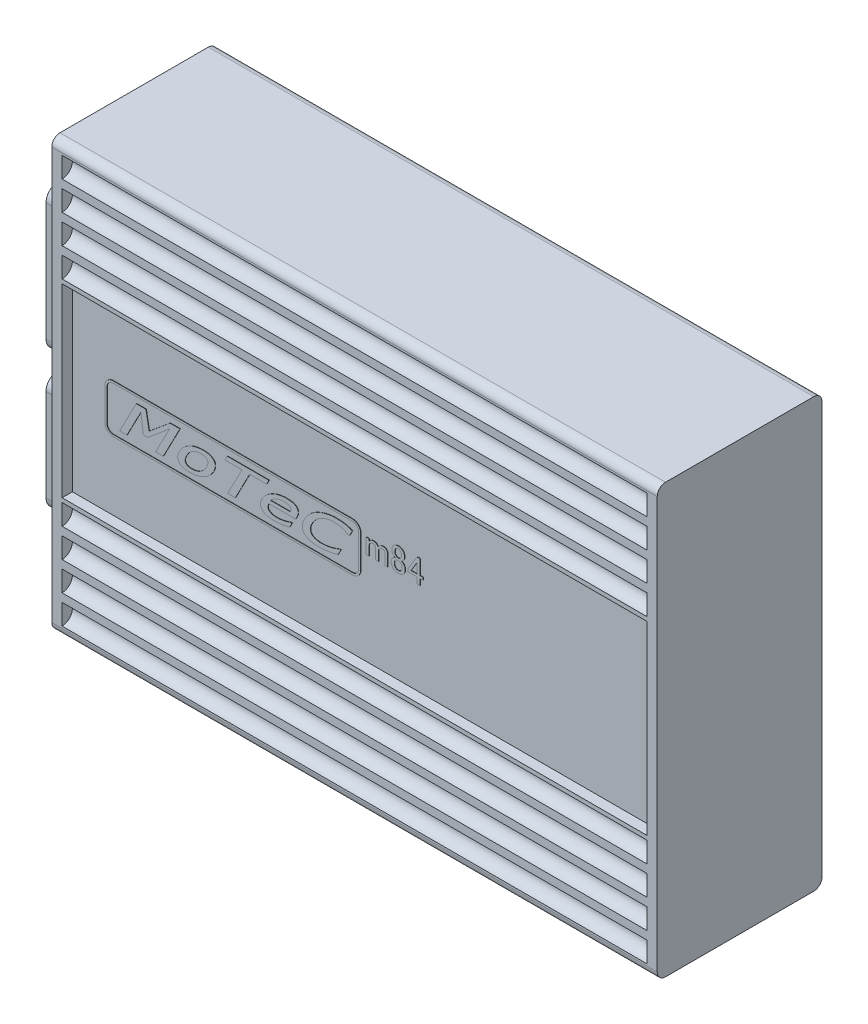
SolidWorks part; units mm, degrees
material "ｽﾁﾚﾝ ﾌﾞﾀｼﾞｴﾝｺﾞﾑ(SBR)"
ref_plane "正面" through (0, 0, 0) normal (0, 0, 1) x (1, 0, 0)
ref_plane "平面" through (0, 0, 0) normal (0, 1, 0) x (1, 0, 0)
ref_plane "右側面" through (0, 0, 0) normal (1, 0, 0) x (0, 0, -1)
sketch "ｽｹｯﾁ1" plane through (0, 0, 0) normal (0, 0, 1) x (1, 0, 0)
  line L1 (-73.5, -52) -> (73.5, -52)
  line L2 (-73.5, -52) -> (-73.5, 52)
  line L3 (-73.5, 52) -> (73.5, 52)
  line L4 (73.5, -52) -> (73.5, 52)
  line L5 (-73.5, -52) -> (73.5, 52) construction
  line L6 (-73.5, 52) -> (73.5, -52) construction
  point P0 (0, 0)
extrude "ﾎﾞｽ - 押し出し1" add sketch "ｽｹｯﾁ1" along normal blind 40
fillet "ﾌｨﾚｯﾄ1" radius 2 4 edges at (0, -52, 0) (0, -52, 40) (0, 52, 0) (0, 52, 40)
sketch "ｽｹｯﾁ5" plane through (0, 0, 0) normal (0, 0, -1) x (-1, 0, 0)
  line L0 (73.5, 50) -> (73.5, -50) construction
  line L1 (-73.5, 22.5) -> (73.5, 22.5)
  line L2 (-73.5, 22.5) -> (-73.5, -22.5)
  line L3 (-73.5, -22.5) -> (73.5, -22.5)
  line L4 (73.5, 22.5) -> (73.5, -22.5)
  line L5 (-73.5, 22.5) -> (73.5, -22.5) construction
  line L6 (-73.5, -22.5) -> (73.5, 22.5) construction
  point P0 (0, 0)
extrude "ｶｯﾄ - 押し出し1" cut sketch "ｽｹｯﾁ5" against normal blind 2.5
sketch "ｽｹｯﾁ6" plane through (-73.5, 0, 0) normal (-1, 0, 0) x (0, 0, 1)
  line L0 (0, 49.5) -> (0, 44.5)
  line L1 (0, 42.5) -> (0, 37.5)
  line L2 (0, 35.5) -> (0, 30.5)
  line L3 (0, 50) -> (0, 22.5) construction
  line L4 (0, 28.5) -> (0, 23.5)
  line L7 (40, 28.5) -> (40, 23.5)
  line L8 (40, 35.5) -> (40, 30.5)
  line L9 (40, 42.5) -> (40, 37.5)
  line L10 (40, 49.5) -> (40, 44.5)
  arc A0 (0, 44.5) -> (0, 49.5) centre (0, 47) ccw
  arc A1 (0, 37.5) -> (0, 42.5) centre (0, 40) ccw
  arc A2 (0, 30.5) -> (0, 35.5) centre (0, 33) ccw
  arc A3 (0, 23.5) -> (0, 28.5) centre (0, 26) ccw
  arc A4 (40, 23.5) -> (40, 28.5) centre (40, 26) cw
  arc A5 (40, 30.5) -> (40, 35.5) centre (40, 33) cw
  arc A6 (40, 37.5) -> (40, 42.5) centre (40, 40) cw
  arc A7 (40, 44.5) -> (40, 49.5) centre (40, 47) cw
extrude "ｶｯﾄ - 押し出し2" cut sketch "ｽｹｯﾁ6" against normal through all
mirror "ﾐﾗｰ1" about plane through (0, 0, 0) normal (0, 1, 0) of "ｶｯﾄ - 押し出し2"
sketch "ｽｹｯﾁ7" plane through (0, 0, 40) normal (0, 0, 1) x (1, 0, 0)
  line L0 (73.5, -23.5) -> (73.5, 23.5) construction
  line L1 (-73.5, -22.5) -> (73.5, -22.5)
  line L2 (-73.5, -22.5) -> (-73.5, 22.5)
  line L3 (-73.5, 22.5) -> (73.5, 22.5)
  line L4 (73.5, -22.5) -> (73.5, 22.5)
  line L5 (-73.5, -22.5) -> (73.5, 22.5) construction
  line L6 (-73.5, 22.5) -> (73.5, -22.5) construction
  point P0 (0, 0)
extrude "ｶｯﾄ - 押し出し3" cut sketch "ｽｹｯﾁ7" against normal blind 2.5
sketch "ｽｹｯﾁ8" plane through (-73.5, 0, 0) normal (-1, 0, 0) x (0, 0, 1)
  line L0 (2, -52) -> (38, -52)
  line L2 (40, -50) -> (40, 50)
  line L3 (38, 52) -> (2, 52)
  line L4 (0, 50) -> (0, -50)
  arc A0 (38, -52) -> (40, -50) centre (38, -50) ccw
  arc A1 (0, -50) -> (2, -52) centre (2, -50) ccw
  arc A2 (2, 52) -> (0, 50) centre (2, 50) ccw
  arc A3 (40, 50) -> (38, 52) centre (38, 50) ccw
  dimension "D1" = 2
extrude "ﾎﾞｽ - 押し出し4" add sketch "ｽｹｯﾁ8" against normal blind 2.5
sketch "ｽｹｯﾁ9" plane through (73.5, 0, 0) normal (1, 0, 0) x (0, 0, -1)
  line L0 (-38, -52) -> (-2, -52)
  line L2 (0, -50) -> (0, 50)
  line L3 (-2, 52) -> (-38, 52)
  line L4 (-40, 50) -> (-40, -50)
  arc A1 (-38, 52) -> (-40, 50) centre (-38, 50) ccw
  arc A2 (0, 50) -> (-2, 52) centre (-2, 50) ccw
  arc A3 (-2, -52) -> (0, -50) centre (-2, -50) ccw
  arc A4 (-40, -50) -> (-38, -52) centre (-38, -50) ccw
  dimension "D1" = 2
extrude "ﾎﾞｽ - 押し出し5" add sketch "ｽｹｯﾁ9" against normal blind 2.5
sketch "ｽｹｯﾁ10" plane through (0, 0, 37.5) normal (0, 0, 1) x (1, 0, 0)
  line L0 (-61, 5.38) -> (-2.9, 5.38)
  line L1 (-61, 5.88) -> (-2.9, 5.88)
  line L2 (-48.818, -3.88) -> (-50.6846, -3.88)
  line L3 (-61, -5.38) -> (-2.9, -5.38)
  line L4 (-50.6846, -3.88) -> (-47.2953, 2.6347)
  line L5 (-62.5, -3.88) -> (-62.5, 3.88)
  line L6 (-63, -3.88) -> (-63, 3.88)
  line L7 (-1.4, 3.88) -> (-1.4, -3.88)
  line L8 (-2.9, -5.88) -> (-61, -5.88)
  line L9 (-0.9, 3.88) -> (-0.9, -3.88)
  line L10 (-47.2953, 2.6347) -> (-52.5742, -1.8169)
  line L11 (-52.5742, -1.8169) -> (-53.6672, -1.8169)
  line L12 (-53.6672, -1.8169) -> (-54.2704, 2.6347)
  line L13 (-54.2704, 2.6347) -> (-57.6598, -3.88)
  line L14 (-57.6598, -3.88) -> (-59.4281, -3.88)
  line L15 (-59.4281, -3.88) -> (-55.3895, 3.8811)
  line L16 (-55.3895, 3.8811) -> (-53.0363, 3.8811)
  line L17 (-53.0363, 3.8811) -> (-52.2641, -0.3464)
  line L18 (-52.2641, -0.3464) -> (-47.1924, 3.8811)
  line L19 (-47.1924, 3.8811) -> (-44.7793, 3.8811)
  line L20 (-44.7793, 3.8811) -> (-48.818, -3.88)
  line L21 (-23.7279, 2.8005) -> (-27.8541, 2.8005)
  line L22 (-27.8541, 2.8005) -> (-31.3309, -3.88)
  line L23 (-31.3309, -3.88) -> (-33.1975, -3.88)
  line L24 (-33.1975, -3.88) -> (-29.7207, 2.8005)
  line L25 (-29.7207, 2.8005) -> (-33.8469, 2.8005)
  line L26 (-33.8469, 2.8005) -> (-33.285, 3.8811)
  line L27 (-33.285, 3.8811) -> (-23.1661, 3.8811)
  line L28 (-23.1661, 3.8811) -> (-23.7279, 2.8005)
  line L29 (-16.6837, -1.031) -> (-23.1677, -1.031)
  line L30 (-17.8457, -2.3081) -> (-17.5448, -2.3081)
  line L31 (-17.5448, -2.3081) -> (-18.1512, -3.4717)
  line L32 (-16.3675, -0.4231) -> (-16.6837, -1.031)
  line L33 (-22.7071, -0.1468) -> (-17.9915, -0.1468)
  line L34 (-2.9053, 3.3592) -> (-3.6052, 2.0145)
  line L35 (-3.6052, 2.0145) -> (-3.9475, 2.0145)
  line L36 (-6.0306, -2.0134) -> (-5.7005, -2.0134)
  line L37 (-5.7005, -2.0134) -> (-6.3944, -3.3458)
  arc A0 (-62.5, -3.88) -> (-61, -5.38) centre (-61, -3.88) ccw
  arc A1 (-63, -3.88) -> (-61, -5.88) centre (-61, -3.88) ccw
  arc A2 (-2.9, -5.38) -> (-1.4, -3.88) centre (-2.9, -3.88) ccw
  arc A3 (-2.9, -5.88) -> (-0.9, -3.88) centre (-2.9, -3.88) ccw
  arc A4 (-0.9, 3.88) -> (-2.9, 5.88) centre (-2.9, 3.88) ccw
  arc A5 (-1.4, 3.88) -> (-2.9, 5.38) centre (-2.9, 3.88) ccw
  arc A6 (-61, 5.38) -> (-62.5, 3.88) centre (-61, 3.88) ccw
  arc A7 (-61, 5.88) -> (-63, 3.88) centre (-61, 3.88) ccw
  spline S0 degree 3 poles (-36.5777, -0.9358) (-36.7009, -1.173) (-36.9152, -1.5135) (-37.2513, -1.9317) (-37.5302, -2.2278) (-37.8372, -2.5041) (-38.1693, -2.764) (-38.5283, -3.0057) (-38.9122, -3.2263) (-39.3132, -3.4265) (-39.7277, -3.6013) (-40.1536, -3.7457) (-40.5887, -3.8684) (-41.0349, -3.9619) (-41.649, -4.05) (-42.1174, -4.0762) (-42.4323, -4.0765) knots 0 0 0 0 0.11486 0.17245 0.230506 0.289545 0.349887 0.411704 0.475483 0.540129 0.604325 0.668756 0.733403 0.798605 0.864633 1 1 1 1
  spline S1 degree 3 poles (-42.4323, -4.0765) (-42.5834, -4.0783) (-42.8056, -4.0683) (-43.0953, -4.0494) (-43.2985, -4.0256) (-43.4923, -3.9973) (-43.6765, -3.96) (-43.8518, -3.9174) (-44.0177, -3.8681) (-44.1746, -3.8138) (-44.3211, -3.7497) (-44.4591, -3.6817) (-44.587, -3.6058) (-44.7062, -3.5246) (-44.8151, -3.4352) (-44.9152, -3.3398) (-45.0063, -3.2387) (-45.0858, -3.1309) (-45.1562, -3.0187) (-45.2118, -2.9001) (-45.2596, -2.778) (-45.2917, -2.6499) (-45.3182, -2.5179) (-45.3269, -2.3804) (-45.3297, -2.2389) (-45.3179, -2.0927) (-45.2961, -1.9415) (-45.2643, -1.7849) (-45.2188, -1.6238) (-45.1639, -1.4575) (-45.0707, -1.2253) (-44.9886, -1.0518) (-44.9282, -0.9358) knots 0 0 0 0 0.08649 0.127322 0.166248 0.203584 0.23944 0.273835 0.30684 0.338533 0.36885 0.398333 0.426574 0.453963 0.480825 0.507145 0.533083 0.558634 0.58376 0.608791 0.633551 0.65871 0.684341 0.710499 0.737457 0.765367 0.794373 0.824886 0.856804 0.89016 0.925145 1 1 1 1
  spline S2 degree 3 poles (-44.9282, -0.9358) (-44.8022, -0.6955) (-44.5877, -0.3482) (-44.2489, 0.0764) (-43.9702, 0.375) (-43.6668, 0.6536) (-43.3382, 0.9124) (-42.9843, 1.1516) (-42.6081, 1.372) (-42.2138, 1.5683) (-41.8079, 1.7417) (-41.3903, 1.8851) (-40.9637, 2.0059) (-40.5266, 2.0973) (-39.9262, 2.1872) (-39.4676, 2.2089) (-39.1596, 2.211) knots 0 0 0 0 0.117897 0.176741 0.23572 0.295189 0.355492 0.41727 0.480633 0.544754 0.608501 0.672263 0.736447 0.800971 0.86614 1 1 1 1
  spline S3 degree 3 poles (-39.1596, 2.211) (-39.0055, 2.212) (-38.7785, 2.2044) (-38.4828, 2.1817) (-38.2753, 2.1594) (-38.0778, 2.128) (-37.8898, 2.0917) (-37.7107, 2.0491) (-37.5419, 1.998) (-37.3816, 1.9418) (-37.2315, 1.8774) (-37.0912, 1.8064) (-36.9598, 1.7299) (-36.8387, 1.645) (-36.7263, 1.5549) (-36.624, 1.4574) (-36.5325, 1.3533) (-36.4501, 1.2439) (-36.3803, 1.1288) (-36.3192, 1.0103) (-36.2719, 0.8865) (-36.2349, 0.7587) (-36.2085, 0.6268) (-36.1952, 0.49) (-36.1917, 0.3489) (-36.2017, 0.2032) (-36.2217, 0.0534) (-36.2531, -0.1007) (-36.2938, -0.26) (-36.3488, -0.4229) (-36.4364, -0.6522) (-36.5191, -0.8216) (-36.5777, -0.9358) knots 0 0 0 0 0.087469 0.128832 0.16828 0.205905 0.2423 0.276956 0.310309 0.342367 0.373332 0.402945 0.431585 0.459541 0.4868 0.513298 0.539635 0.565367 0.590919 0.615986 0.640903 0.665995 0.691455 0.717145 0.74387 0.771515 0.799937 0.829554 0.860759 0.893179 0.927103 1 1 1 1
  spline S4 degree 3 poles (-38.346, -0.9358) (-38.2574, -0.7704) (-38.1489, -0.5248) (-38.0457, -0.2002) (-38.0049, 0.0143) (-37.9926, 0.211) (-38.0094, 0.3913) (-38.0597, 0.5536) (-38.1369, 0.6994) (-38.2448, 0.8249) (-38.3747, 0.9354) (-38.5316, 1.0255) (-38.7113, 1.1012) (-38.9167, 1.1584) (-39.2379, 1.2147) (-39.4932, 1.2305) (-39.6708, 1.2286) knots 0 0 0 0 0.165351 0.236136 0.299935 0.35732 0.409486 0.458578 0.506215 0.55393 0.603552 0.655936 0.712748 0.775154 0.843472 1 1 1 1
  spline S5 degree 3 poles (-39.6708, 1.2286) (-39.8529, 1.2297) (-40.1234, 1.2126) (-40.4773, 1.1597) (-40.7328, 1.103) (-40.9807, 1.0286) (-41.2218, 0.9397) (-41.4561, 0.8354) (-41.6821, 0.7134) (-41.9013, 0.5755) (-42.11, 0.417) (-42.309, 0.2388) (-42.4999, 0.0427) (-42.6788, -0.1755) (-42.9131, -0.4938) (-43.0653, -0.7549) (-43.1599, -0.9358) knots 0 0 0 0 0.125748 0.186879 0.246987 0.306363 0.365517 0.424368 0.483349 0.542766 0.603061 0.664139 0.727124 0.791879 0.858893 1 1 1 1
  spline S6 degree 3 poles (-43.1599, -0.9358) (-43.2444, -1.1024) (-43.3583, -1.3453) (-43.4595, -1.6697) (-43.5022, -1.8833) (-43.5179, -2.0794) (-43.5036, -2.2592) (-43.4591, -2.4214) (-43.3855, -2.5663) (-43.2836, -2.6915) (-43.1582, -2.8004) (-43.0096, -2.8929) (-42.8366, -2.9656) (-42.6417, -3.0243) (-42.335, -3.08) (-42.0911, -3.096) (-41.9211, -3.0941) knots 0 0 0 0 0.168476 0.240795 0.305611 0.364297 0.417506 0.467272 0.514892 0.562763 0.611762 0.663944 0.719687 0.780349 0.846975 1 1 1 1
  spline S7 degree 3 poles (-41.9211, -3.0941) (-41.7331, -3.0918) (-41.4531, -3.0796) (-41.0877, -3.0195) (-40.8225, -2.963) (-40.5649, -2.885) (-40.3148, -2.7913) (-40.0706, -2.6823) (-39.8349, -2.5547) (-39.6073, -2.4111) (-39.3924, -2.2487) (-39.1871, -2.0723) (-38.995, -1.8776) (-38.8135, -1.6672) (-38.5852, -1.3596) (-38.4377, -1.1088) (-38.346, -0.9358) knots 0 0 0 0 0.128096 0.190164 0.251852 0.312564 0.373178 0.433506 0.494435 0.555497 0.616445 0.67768 0.739494 0.802466 0.866689 1 1 1 1
  spline S8 degree 3 poles (-23.1677, -1.031) (-23.239, -1.1708) (-23.3273, -1.3838) (-23.38, -1.6756) (-23.3836, -1.8779) (-23.3558, -2.064) (-23.2898, -2.2835) (-23.1916, -2.4213) (-23.1124, -2.4939) knots 0 0 0 0 0.300432 0.436419 0.564515 0.685087 0.794857 1 1 1 1
  spline S9 degree 3 poles (-23.1124, -2.4939) (-23.0171, -2.5853) (-22.8472, -2.6978) (-22.5932, -2.8134) (-22.3737, -2.881) (-22.1311, -2.9328) (-21.7617, -2.9823) (-21.4713, -2.9964) (-21.2704, -2.9958) knots 0 0 0 0 0.202 0.310705 0.427794 0.554064 0.691352 1 1 1 1
  spline S10 degree 3 poles (-21.2704, -2.9958) (-20.9645, -2.9964) (-20.4966, -2.9651) (-19.8657, -2.8697) (-19.4578, -2.787) (-19.1335, -2.7124) (-18.904, -2.6537) (-18.6896, -2.5968) (-18.4904, -2.5414) (-18.3075, -2.4814) (-18.0917, -2.4113) (-17.9411, -2.3484) (-17.8457, -2.3081) knots 0 0 0 0 0.261145 0.399928 0.544803 0.616587 0.684226 0.7471 0.806182 0.860786 0.911516 1 1 1 1
  spline S11 degree 3 poles (-18.1512, -3.4717) (-18.475, -3.5472) (-18.9516, -3.6513) (-19.5758, -3.7713) (-20.0167, -3.8464) (-20.4491, -3.9062) (-21.0272, -3.9606) (-21.4634, -3.9803) (-21.7554, -3.9782) knots 0 0 0 0 0.273424 0.401082 0.522686 0.641161 0.759937 1 1 1 1
  spline S12 degree 3 poles (-21.7554, -3.9782) (-21.9325, -3.9782) (-22.1927, -3.9728) (-22.5319, -3.952) (-22.7704, -3.9305) (-22.9983, -3.9034) (-23.2158, -3.8692) (-23.4231, -3.8303) (-23.6188, -3.7821) (-23.8044, -3.7301) (-23.9792, -3.6721) (-24.1438, -3.6078) (-24.2976, -3.5371) (-24.4413, -3.4607) (-24.5728, -3.3758) (-24.6951, -3.287) (-24.8059, -3.1914) (-24.9057, -3.0909) (-24.9926, -2.984) (-25.0668, -2.8714) (-25.1282, -2.7529) (-25.1775, -2.6295) (-25.2152, -2.5012) (-25.2374, -2.3672) (-25.2483, -2.228) (-25.2465, -2.0837) (-25.2323, -1.9339) (-25.2059, -1.779) (-25.1677, -1.6188) (-25.1143, -1.4541) (-25.0259, -1.2206) (-24.9444, -1.0463) (-24.8838, -0.9297) knots 0 0 0 0 0.093747 0.137709 0.179862 0.220513 0.259166 0.296403 0.332074 0.365856 0.398404 0.429538 0.459352 0.487951 0.5156 0.542146 0.567881 0.592971 0.617041 0.640704 0.664206 0.687544 0.710946 0.734858 0.759308 0.78477 0.811155 0.838897 0.867868 0.898277 0.930422 1 1 1 1
  spline S13 degree 3 poles (-24.8838, -0.9297) (-24.7596, -0.6889) (-24.54, -0.3451) (-24.1967, 0.0779) (-23.9084, 0.374) (-23.5931, 0.6518) (-23.2507, 0.9114) (-22.879, 1.1507) (-22.4832, 1.3708) (-22.0683, 1.5667) (-21.6416, 1.7397) (-21.2059, 1.8857) (-20.7601, 2.0035) (-20.3058, 2.0979) (-19.6825, 2.1863) (-19.2078, 2.2093) (-18.8895, 2.211) knots 0 0 0 0 0.114335 0.17179 0.229874 0.288677 0.349154 0.411205 0.475256 0.540323 0.604903 0.66963 0.734274 0.799596 0.865529 1 1 1 1
  spline S14 degree 3 poles (-18.8895, 2.211) (-18.6048, 2.2099) (-18.1943, 2.1957) (-17.6759, 2.1191) (-17.3417, 2.0438) (-17.0445, 1.9461) (-16.7843, 1.8273) (-16.5608, 1.6854) (-16.3763, 1.5207) (-16.2307, 1.3359) (-16.1253, 1.1324) (-16.062, 0.9113) (-16.0409, 0.6734) (-16.0638, 0.4205) (-16.1471, 0.0427) (-16.2705, -0.2361) (-16.3675, -0.4231) knots 0 0 0 0 0.180062 0.258847 0.330846 0.396281 0.456168 0.511145 0.562887 0.611718 0.659004 0.706791 0.756144 0.809012 0.866596 1 1 1 1
  spline S15 degree 3 poles (-17.9915, -0.1468) (-17.9461, -0.0555) (-17.8865, 0.0815) (-17.8527, 0.2692) (-17.8447, 0.3975) (-17.8607, 0.5196) (-17.8964, 0.6349) (-17.9525, 0.7434) (-18.0288, 0.8451) (-18.1292, 0.9365) (-18.2534, 1.0168) (-18.4034, 1.0814) (-18.5763, 1.1374) (-18.7753, 1.1766) (-19.0885, 1.2199) (-19.3376, 1.2281) (-19.5112, 1.2286) knots 0 0 0 0 0.116957 0.168662 0.217232 0.263196 0.308491 0.3545 0.402079 0.452957 0.508728 0.570212 0.638975 0.71601 0.801566 1 1 1 1
  spline S16 degree 3 poles (-19.5112, 1.2286) (-19.6901, 1.2296) (-19.9551, 1.2158) (-20.3024, 1.173) (-20.5519, 1.1269) (-20.7942, 1.0681) (-21.0289, 0.9984) (-21.2559, 0.9133) (-21.473, 0.8155) (-21.6796, 0.7097) (-21.8724, 0.5999) (-22.0503, 0.4864) (-22.2113, 0.3673) (-22.3597, 0.2473) (-22.5306, 0.0813) (-22.6436, -0.052) (-22.7071, -0.1468) knots 0 0 0 0 0.148913 0.22062 0.291229 0.360047 0.428112 0.494978 0.561724 0.626315 0.68814 0.746401 0.801873 0.85484 0.905156 1 1 1 1
  spline S17 degree 3 poles (-6.3944, -3.3458) (-6.5902, -3.3974) (-6.8702, -3.4618) (-7.2185, -3.5552) (-7.4427, -3.6129) (-7.6661, -3.6705) (-8.0166, -3.7476) (-8.2963, -3.8041) (-8.4943, -3.8416) knots 0 0 0 0 0.281526 0.399182 0.501308 0.603258 0.719903 1 1 1 1
  spline S18 degree 3 poles (-8.4943, -3.8416) (-8.8676, -3.9077) (-9.3444, -3.9804) (-9.9296, -4.0402) (-10.362, -4.069) (-10.6924, -4.0756) (-10.9166, -4.0765) knots 0 0 0 0 0.466732 0.593333 0.724013 1 1 1 1
  spline S19 degree 3 poles (-10.9166, -4.0765) (-11.1224, -4.0785) (-11.4255, -4.0686) (-11.8221, -4.0444) (-12.1026, -4.0187) (-12.3717, -3.9842) (-12.6302, -3.9457) (-12.8771, -3.8954) (-13.1137, -3.8416) (-13.3375, -3.777) (-13.5489, -3.7043) (-13.7484, -3.6255) (-13.9349, -3.5367) (-14.1073, -3.4372) (-14.3203, -3.2993) (-14.4632, -3.1767) (-14.5515, -3.091) knots 0 0 0 0 0.160141 0.235948 0.30913 0.379362 0.447054 0.512417 0.575391 0.635885 0.693558 0.74931 0.80274 0.854105 0.904135 1 1 1 1
  spline S20 degree 3 poles (-14.5515, -3.091) (-14.6332, -3.0081) (-14.7451, -2.8747) (-14.8665, -2.6775) (-14.9392, -2.5203) (-14.9998, -2.3557) (-15.0445, -2.1824) (-15.0729, -2.0004) (-15.0888, -1.8101) (-15.0872, -1.6112) (-15.0661, -1.4045) (-15.0293, -1.1901) (-14.9748, -0.9675) (-14.9028, -0.7377) (-14.7767, -0.413) (-14.6637, -0.1699) (-14.5792, -0.0071) knots 0 0 0 0 0.105347 0.15689 0.209093 0.261831 0.315407 0.370754 0.428362 0.488101 0.550445 0.616222 0.684847 0.757639 0.834008 1 1 1 1
  spline S21 degree 3 poles (-14.5792, -0.0071) (-14.4951, 0.1549) (-14.3581, 0.3917) (-14.1569, 0.6954) (-13.9973, 0.9172) (-13.8265, 1.1317) (-13.6473, 1.3406) (-13.4578, 1.5424) (-13.1913, 1.8022) (-12.8362, 2.1099) (-12.2254, 2.5699) (-11.7239, 2.8586) (-11.3786, 3.0338) knots 0 0 0 0 0.121978 0.18268 0.243425 0.304524 0.365875 0.427326 0.489476 0.614555 0.741086 1 1 1 1
  spline S22 degree 3 poles (-11.3786, 3.0338) (-11.0336, 3.2049) (-10.496, 3.4343) (-9.7453, 3.668) (-9.1567, 3.8174) (-8.5507, 3.9325) (-7.7204, 4.0477) (-7.0883, 4.0758) (-6.6645, 4.0776) knots 0 0 0 0 0.237239 0.359144 0.483968 0.611049 0.738924 1 1 1 1
  spline S23 degree 3 poles (-6.6645, 4.0776) (-6.3521, 4.0784) (-5.8883, 4.0593) (-5.2793, 3.995) (-4.8316, 3.9292) (-4.3774, 3.8355) (-3.7276, 3.6632) (-3.2372, 3.49) (-2.9053, 3.3592) knots 0 0 0 0 0.243327 0.361127 0.476764 0.595548 0.722064 1 1 1 1
  spline S24 degree 3 poles (-3.9475, 2.0145) (-4.1771, 2.184) (-4.5416, 2.4084) (-5.0614, 2.6382) (-5.4679, 2.7721) (-5.8967, 2.874) (-6.5232, 2.9708) (-7.0117, 2.9991) (-7.3461, 2.9969) knots 0 0 0 0 0.237578 0.354907 0.472536 0.593451 0.721574 1 1 1 1
  spline S25 degree 3 poles (-7.3461, 2.9969) (-7.6219, 2.9979) (-8.0311, 2.9755) (-8.5665, 2.9016) (-8.9542, 2.8232) (-9.3368, 2.7185) (-9.8553, 2.5457) (-10.2318, 2.368) (-10.4822, 2.2417) knots 0 0 0 0 0.253906 0.376619 0.497274 0.617832 0.741623 1 1 1 1
  spline S26 degree 3 poles (-10.4822, 2.2417) (-10.7045, 2.1261) (-11.028, 1.9227) (-11.4317, 1.6025) (-11.7296, 1.3332) (-12.0114, 1.0365) (-12.3621, 0.6006) (-12.5845, 0.2402) (-12.7156, -0.0117) knots 0 0 0 0 0.233293 0.354756 0.479582 0.607001 0.735458 1 1 1 1
  spline S27 degree 3 poles (-12.7156, -0.0117) (-12.7817, -0.1391) (-12.8725, -0.3274) (-12.9672, -0.5803) (-13.0257, -0.7553) (-13.0665, -0.9239) (-13.0951, -1.0849) (-13.1092, -1.2379) (-13.1092, -1.4273) (-13.0816, -1.6452) (-13.0027, -1.9554) (-12.8863, -2.1582) (-12.7862, -2.2682) knots 0 0 0 0 0.179369 0.260704 0.337327 0.409738 0.477214 0.541403 0.601498 0.713544 0.814809 1 1 1 1
  spline S28 degree 3 poles (-12.7862, -2.2682) (-12.6661, -2.3989) (-12.4496, -2.5673) (-12.1148, -2.7325) (-11.8285, -2.8305) (-11.5157, -2.9045) (-11.0545, -2.9772) (-10.6945, -2.996) (-10.4484, -2.9958) knots 0 0 0 0 0.211163 0.323577 0.443788 0.571197 0.706507 1 1 1 1
  spline S29 degree 3 poles (-10.4484, -2.9958) (-10.0792, -2.9962) (-9.5258, -2.9642) (-8.7927, -2.864) (-8.244, -2.7575) (-7.6933, -2.6209) (-6.9482, -2.3886) (-6.3948, -2.1771) (-6.0306, -2.0134) knots 0 0 0 0 0.24289 0.364219 0.486645 0.610525 0.737368 1 1 1 1
sketch "ｽｹｯﾁ11" plane through (0, 0, 37.5) normal (0, 0, 1) x (1, 0, 0)
  line L0 (1.1441, 0.0981) -> (0.448, 0.0981)
  line L1 (0.448, 0.0981) -> (0.448, 3.7593)
  line L2 (0.448, 3.7593) -> (1.1441, 3.7593)
  line L3 (1.1441, 3.7593) -> (1.1441, 3.2036)
  line L4 (5.6553, 2.8113) -> (5.6553, 0.0981)
  line L5 (5.6553, 0.0981) -> (4.9592, 0.0981)
  line L6 (4.9592, 0.0981) -> (4.9592, 2.6806)
  line L7 (3.3997, 2.419) -> (3.3997, 0.0981)
  line L8 (3.3997, 0.0981) -> (2.7036, 0.0981)
  line L9 (2.7036, 0.0981) -> (2.7036, 2.6479)
  line L10 (1.1441, 2.3864) -> (1.1441, 0.0981)
  line L11 (8.9655, 3.0075) -> (8.9655, 2.9421)
  line L12 (7.4618, 2.9421) -> (7.4618, 3.0075)
  line L13 (12.7902, 5.7534) -> (13.5421, 5.7534)
  line L14 (13.5421, 5.7534) -> (13.5421, 2.1575)
  line L15 (13.5421, 2.1575) -> (14.2286, 2.1575)
  line L16 (14.2286, 2.1575) -> (14.2286, 1.5388)
  line L17 (14.2286, 1.5388) -> (13.5421, 1.5388)
  line L18 (13.5421, 1.5388) -> (13.5421, 0.0981)
  line L19 (13.5421, 0.0981) -> (12.7684, 0.0981)
  line L20 (12.7684, 0.0981) -> (12.7684, 1.5388)
  line L21 (12.7684, 1.5388) -> (10.6, 1.5388)
  line L22 (10.6, 1.5388) -> (10.6, 2.1902)
  line L23 (10.6, 2.1902) -> (12.7902, 5.7534)
  line L24 (12.7684, 4.5439) -> (11.3192, 2.1575)
  line L25 (11.3192, 2.1575) -> (12.7684, 2.1575)
  line L26 (12.7684, 2.1575) -> (12.7684, 4.5439)
  spline S0 degree 3 poles (1.1441, 3.2036) (1.2091, 3.3006) (1.3165, 3.4324) (1.4761, 3.5832) (1.5982, 3.6709) (1.7237, 3.7398) (1.8965, 3.8054) (2.0336, 3.8248) (2.1248, 3.8247) knots 0 0 0 0 0.289076 0.420056 0.543346 0.660649 0.774007 1 1 1 1
  spline S1 degree 3 poles (2.1248, 3.8247) (2.2225, 3.8255) (2.3653, 3.8154) (2.5475, 3.7813) (2.6714, 3.7462) (2.7859, 3.7001) (2.9253, 3.6249) (3.0183, 3.5525) (3.0728, 3.4978) knots 0 0 0 0 0.28435 0.416051 0.539631 0.658871 0.775162 1 1 1 1
  spline S2 degree 3 poles (3.0728, 3.4978) (3.1259, 3.4441) (3.225, 3.3321) (3.3007, 3.2031) (3.3344, 3.1382) knots 0 0 0 0 0.508066 1 1 1 1
  spline S3 degree 3 poles (3.3344, 3.1382) (3.4009, 3.2461) (3.5142, 3.3952) (3.6946, 3.5595) (3.8391, 3.6553) (3.9921, 3.7317) (4.2138, 3.8066) (4.3918, 3.8235) (4.5112, 3.8247) knots 0 0 0 0 0.266156 0.390354 0.510676 0.628903 0.748675 1 1 1 1
  spline S4 degree 3 poles (4.5112, 3.8247) (4.5937, 3.8239) (4.715, 3.8171) (4.8701, 3.7856) (4.9763, 3.7531) (5.0759, 3.7116) (5.1981, 3.6443) (5.2797, 3.579) (5.3284, 3.5305) knots 0 0 0 0 0.277854 0.406706 0.531659 0.650908 0.768781 1 1 1 1
  spline S5 degree 3 poles (5.3284, 3.5305) (5.3803, 3.4787) (5.4513, 3.3967) (5.5288, 3.2784) (5.576, 3.1891) (5.6103, 3.0972) (5.6454, 2.9726) (5.6558, 2.876) (5.6553, 2.8113) knots 0 0 0 0 0.271081 0.399345 0.522112 0.643458 0.761079 1 1 1 1
  spline S6 degree 3 poles (4.9592, 2.6806) (4.9575, 2.7409) (4.949, 2.8568) (4.9009, 2.9629) (4.8708, 3.0075) knots 0 0 0 0 0.529898 1 1 1 1
  spline S7 degree 3 poles (4.8708, 3.0075) (4.81, 3.0685) (4.6691, 3.1722) (4.4969, 3.2038) (4.4131, 3.2036) knots 0 0 0 0 0.507506 1 1 1 1
  spline S8 degree 3 poles (4.4131, 3.2036) (4.3398, 3.2028) (4.2315, 3.1955) (4.0927, 3.1647) (3.9963, 3.131) (3.9039, 3.0907) (3.7882, 3.0211) (3.7089, 2.9578) (3.6613, 2.9094) knots 0 0 0 0 0.265315 0.391024 0.512886 0.634416 0.754828 1 1 1 1
  spline S9 degree 3 poles (3.6613, 2.9094) (3.5876, 2.833) (3.4593, 2.6878) (3.4011, 2.5024) (3.3997, 2.419) knots 0 0 0 0 0.564258 1 1 1 1
  spline S10 degree 3 poles (2.7036, 2.6479) (2.7041, 2.7153) (2.672, 2.8568) (2.5978, 2.9811) (2.5498, 3.0402) knots 0 0 0 0 0.468245 1 1 1 1
  spline S11 degree 3 poles (2.5498, 3.0402) (2.4931, 3.098) (2.3343, 3.1836) (2.1559, 3.2052) (2.0595, 3.2036) knots 0 0 0 0 0.45309 1 1 1 1
  spline S12 degree 3 poles (2.0595, 3.2036) (1.9447, 3.2054) (1.7132, 3.1598) (1.5193, 3.0255) (1.4384, 2.9421) knots 0 0 0 0 0.496526 1 1 1 1
  spline S13 degree 3 poles (1.4384, 2.9421) (1.3545, 2.8562) (1.2127, 2.6903) (1.1432, 2.4818) (1.1441, 2.3864) knots 0 0 0 0 0.561835 1 1 1 1
  spline S14 degree 3 poles (6.6772, 4.1843) (6.6768, 4.2995) (6.6912, 4.4688) (6.7381, 4.6867) (6.7896, 4.838) (6.8539, 4.9823) (6.9595, 5.1641) (7.0598, 5.287) (7.1349, 5.3611) knots 0 0 0 0 0.266281 0.391515 0.514598 0.635338 0.756207 1 1 1 1
  spline S15 degree 3 poles (7.1349, 5.3611) (7.2002, 5.4253) (7.3073, 5.5139) (7.4705, 5.6021) (7.6011, 5.6584) (7.7419, 5.7001) (7.9453, 5.7439) (8.1052, 5.7528) (8.2136, 5.7534) knots 0 0 0 0 0.233399 0.350616 0.471182 0.594645 0.723766 1 1 1 1
  spline S16 degree 3 poles (8.2136, 5.7534) (8.3232, 5.7551) (8.4841, 5.7404) (8.6912, 5.6974) (8.8344, 5.6494) (8.9701, 5.5899) (9.1412, 5.4928) (9.2549, 5.3974) (9.3251, 5.3284) knots 0 0 0 0 0.268573 0.395226 0.518308 0.638476 0.758247 1 1 1 1
  spline S17 degree 3 poles (9.3251, 5.3284) (9.3942, 5.2575) (9.4892, 5.1424) (9.5874, 4.969) (9.6459, 4.8292) (9.694, 4.6812) (9.7374, 4.466) (9.7518, 4.2987) (9.75, 4.1843) knots 0 0 0 0 0.237237 0.354867 0.475589 0.599283 0.726563 1 1 1 1
  spline S18 degree 3 poles (9.75, 4.1843) (9.7496, 4.0948) (9.7399, 3.9612) (9.6961, 3.7908) (9.6544, 3.6685) (9.5976, 3.5525) (9.5084, 3.4007) (9.4204, 3.3) (9.3578, 3.2363) knots 0 0 0 0 0.255144 0.378267 0.499952 0.622216 0.745323 1 1 1 1
  spline S19 degree 3 poles (9.3578, 3.2363) (9.3031, 3.1841) (9.1835, 3.0859) (9.0392, 3.0294) (8.9655, 3.0075) knots 0 0 0 0 0.495336 1 1 1 1
  spline S20 degree 3 poles (8.9655, 2.9421) (9.0661, 2.92) (9.2702, 2.8364) (9.4397, 2.6957) (9.5212, 2.6152) knots 0 0 0 0 0.472373 1 1 1 1
  spline S21 degree 3 poles (9.5212, 2.6152) (9.5855, 2.5508) (9.6734, 2.4449) (9.7619, 2.2847) (9.8183, 2.1578) (9.86, 2.0219) (9.904, 1.8266) (9.9129, 1.6731) (9.9135, 1.5691) knots 0 0 0 0 0.238094 0.356648 0.477581 0.600363 0.727833 1 1 1 1
  spline S22 degree 3 poles (9.9135, 1.5691) (9.9138, 1.4636) (9.8992, 1.3074) (9.852, 1.1064) (9.8021, 0.9634) (9.7365, 0.8269) (9.6294, 0.6512) (9.5306, 0.5307) (9.4558, 0.4577) knots 0 0 0 0 0.256258 0.379192 0.500731 0.623509 0.746244 1 1 1 1
  spline S23 degree 3 poles (9.4558, 0.4577) (9.3839, 0.3872) (9.2639, 0.2913) (9.0813, 0.1952) (8.9312, 0.1362) (8.7694, 0.0881) (8.5294, 0.0453) (8.3421, 0.0307) (8.2136, 0.0327) knots 0 0 0 0 0.224285 0.339224 0.458169 0.582683 0.714303 1 1 1 1
  spline S24 degree 3 poles (8.2136, 0.0327) (8.0851, 0.0307) (7.8978, 0.0453) (7.6578, 0.0881) (7.496, 0.1362) (7.346, 0.1952) (7.1634, 0.2913) (7.0434, 0.3872) (6.9714, 0.4577) knots 0 0 0 0 0.285697 0.417317 0.541831 0.660776 0.775715 1 1 1 1
  spline S25 degree 3 poles (6.9714, 0.4577) (6.8964, 0.5307) (6.7982, 0.6513) (6.6904, 0.8266) (6.627, 0.964) (6.5748, 1.1061) (6.5284, 1.3075) (6.5133, 1.4635) (6.5138, 1.5691) knots 0 0 0 0 0.253779 0.376526 0.498895 0.620773 0.743719 1 1 1 1
  spline S26 degree 3 poles (6.5138, 1.5691) (6.5144, 1.6731) (6.5233, 1.8266) (6.5672, 2.0219) (6.6089, 2.1578) (6.6653, 2.2847) (6.7538, 2.4449) (6.8418, 2.5508) (6.906, 2.6152) knots 0 0 0 0 0.272167 0.399637 0.522419 0.643352 0.761906 1 1 1 1
  spline S27 degree 3 poles (6.906, 2.6152) (6.9876, 2.6957) (7.157, 2.8364) (7.3611, 2.92) (7.4618, 2.9421) knots 0 0 0 0 0.527627 1 1 1 1
  spline S28 degree 3 poles (7.4618, 3.0075) (7.3877, 3.0309) (7.2361, 3.1183) (7.1052, 3.2335) (7.0368, 3.3017) knots 0 0 0 0 0.44402 1 1 1 1
  spline S29 degree 3 poles (7.0368, 3.3017) (6.9775, 3.359) (6.8997, 3.4543) (6.8161, 3.5935) (6.7647, 3.7015) (6.7261, 3.815) (6.6881, 3.9751) (6.6777, 4.1) (6.6772, 4.1843) knots 0 0 0 0 0.252388 0.374951 0.496631 0.618235 0.741494 1 1 1 1
  spline S30 degree 3 poles (8.2136, 5.165) (8.1109, 5.1645) (7.9026, 5.1302) (7.7302, 5.0084) (7.6579, 4.9362) knots 0 0 0 0 0.501621 1 1 1 1
  spline S31 degree 3 poles (7.6579, 4.9362) (7.6128, 4.8936) (7.5577, 4.8176) (7.4959, 4.7079) (7.4599, 4.6164) (7.4303, 4.519) (7.4054, 4.3741) (7.3943, 4.2619) (7.3964, 4.1843) knots 0 0 0 0 0.226302 0.342995 0.461285 0.586435 0.716023 1 1 1 1
  spline S32 degree 3 poles (7.3964, 4.1843) (7.394, 4.1115) (7.4059, 4.0058) (7.43, 3.8692) (7.4606, 3.7766) (7.4959, 3.6885) (7.558, 3.5813) (7.614, 3.5078) (7.6579, 3.4651) knots 0 0 0 0 0.276896 0.405601 0.528379 0.64854 0.7672 1 1 1 1
  spline S33 degree 3 poles (7.6579, 3.4651) (7.7283, 3.3938) (7.8899, 3.2759) (8.086, 3.2362) (8.1809, 3.2363) knots 0 0 0 0 0.514333 1 1 1 1
  spline S34 degree 3 poles (8.1809, 3.2363) (8.2968, 3.2356) (8.5112, 3.26) (8.7019, 3.3629) (8.7694, 3.4324) knots 0 0 0 0 0.548333 1 1 1 1
  spline S35 degree 3 poles (8.7694, 3.4324) (8.8134, 3.476) (8.8717, 3.5499) (8.931, 3.6611) (8.9676, 3.7521) (8.9964, 3.8498) (9.0247, 3.994) (9.0311, 4.107) (9.0309, 4.1843) knots 0 0 0 0 0.227087 0.343044 0.461305 0.586425 0.716259 1 1 1 1
  spline S36 degree 3 poles (9.0309, 4.1843) (9.0311, 4.2616) (9.0247, 4.3746) (8.9964, 4.5188) (8.9676, 4.6165) (8.931, 4.7075) (8.8717, 4.8187) (8.8134, 4.8926) (8.7694, 4.9362) knots 0 0 0 0 0.283741 0.413575 0.538695 0.656956 0.772913 1 1 1 1
  spline S37 degree 3 poles (8.7694, 4.9362) (8.6971, 5.0084) (8.5246, 5.1302) (8.3164, 5.1645) (8.2136, 5.165) knots 0 0 0 0 0.498379 1 1 1 1
  spline S38 degree 3 poles (8.2136, 2.6806) (8.146, 2.681) (8.0463, 2.6739) (7.9185, 2.6461) (7.83, 2.6166) (7.7457, 2.5804) (7.6401, 2.5205) (7.5699, 2.462) (7.5271, 2.419) knots 0 0 0 0 0.268893 0.395355 0.518592 0.639256 0.759204 1 1 1 1
  spline S39 degree 3 poles (7.5271, 2.419) (7.482, 2.3764) (7.427, 2.3005) (7.3651, 2.1908) (7.3291, 2.0993) (7.2996, 2.0019) (7.2746, 1.857) (7.2635, 1.7448) (7.2656, 1.6672) knots 0 0 0 0 0.226302 0.342995 0.461285 0.586435 0.716023 1 1 1 1
  spline S40 degree 3 poles (7.2656, 1.6672) (7.2661, 1.5894) (7.2737, 1.4748) (7.3044, 1.3279) (7.338, 1.2265) (7.3782, 1.1304) (7.4478, 1.0119) (7.5102, 0.9302) (7.5598, 0.8826) knots 0 0 0 0 0.271133 0.39916 0.521948 0.642942 0.761423 1 1 1 1
  spline S41 degree 3 poles (7.5598, 0.8826) (7.6014, 0.8388) (7.6726, 0.7847) (7.773, 0.7208) (7.8539, 0.6856) (7.9376, 0.6551) (8.058, 0.631) (8.1504, 0.6188) (8.2136, 0.6211) knots 0 0 0 0 0.248911 0.370594 0.49191 0.614156 0.73921 1 1 1 1
  spline S42 degree 3 poles (8.2136, 0.6211) (8.2768, 0.6188) (8.3692, 0.631) (8.4896, 0.6551) (8.5733, 0.6856) (8.6543, 0.7208) (8.7546, 0.7847) (8.8259, 0.8388) (8.8674, 0.8826) knots 0 0 0 0 0.26079 0.385844 0.50809 0.629406 0.751089 1 1 1 1
  spline S43 degree 3 poles (8.8674, 0.8826) (8.917, 0.9302) (8.9794, 1.0119) (9.049, 1.1304) (9.0892, 1.2265) (9.1228, 1.3279) (9.1535, 1.4748) (9.1611, 1.5894) (9.1616, 1.6672) knots 0 0 0 0 0.238577 0.357058 0.478052 0.60084 0.728867 1 1 1 1
  spline S44 degree 3 poles (9.1616, 1.6672) (9.161, 1.7449) (9.1536, 1.8597) (9.1226, 2.0068) (9.0898, 2.1085) (9.0486, 2.2042) (8.9795, 2.3225) (8.917, 2.4042) (8.8674, 2.4517) knots 0 0 0 0 0.27112 0.399141 0.523262 0.642959 0.761434 1 1 1 1
  spline S45 degree 3 poles (8.8674, 2.4517) (8.8284, 2.4889) (8.7651, 2.5418) (8.6675, 2.592) (8.5893, 2.6264) (8.5033, 2.6489) (8.3784, 2.6748) (8.2803, 2.6803) (8.2136, 2.6806) knots 0 0 0 0 0.228211 0.343996 0.462271 0.587869 0.718102 1 1 1 1
extrude "ﾎﾞｽ - 押し出し6" add sketch "ｽｹｯﾁ11" along normal blind 0.1
extrude "ﾎﾞｽ - 押し出し7" add sketch "ｽｹｯﾁ10" along normal blind 0.1 contours L20 L19 L18 L17 L16 L15 L14 L13 L12 L11 L10 L4 L2 | S3 S2 S1 S0 S7 S6 S5 S4 | L28 L27 L26 L25 L24 L23 L22 L21 | S14 S13 S12 S11 L31 L30 S10 S9 S8 L29 L32 S16 S15 L33 | S29 S28 S27 S26 S25 S24 L35 L34 S23 S22 S21 S20 S19 S18 S17 L37 L36 | L1 A7 L6 A1 L8 A3 L9 A4 A6 L0 A5 L7 A2 L3 A0 L5
sketch "ｽｹｯﾁ12" plane through (-73.5, 0, 0) normal (-1, 0, 0) x (0, 0, 1)
  line L0 (38, 52) -> (2, 52) construction
  line L1 (10.2, 34.6) -> (34, 34.6)
  line L2 (10.2, 34.6) -> (10.2, -0.1)
  line L3 (10.2, -0.1) -> (34, -0.1)
  line L4 (34, 34.6) -> (34, -0.1)
  line L5 (10.2, -5.1) -> (34, -5.1)
  line L6 (10.2, -5.1) -> (10.2, -33.5)
  line L7 (10.2, -33.5) -> (34, -33.5)
  line L8 (34, -5.1) -> (34, -33.5)
  line L9 (0, 50) -> (0, -50) construction
  line L10 (38, -52) -> (2, -52) construction
  point P8 (20, 52)
  dimension "D1" = 34.7
  dimension "D2" = 23.8
  dimension "D3" = 17.4
  dimension "D4" = 10.2
  dimension "D5" = 28.4
  dimension "D6" = 18.5
  dimension "D7" = 23.8
  dimension "D8" = 10.2
extrude "ﾎﾞｽ - 押し出し8" add sketch "ｽｹｯﾁ12" along normal blind 7.4
sketch "ｽｹｯﾁ14" plane through (-80.9, 0, 0) normal (-1, 0, 0) x (0, 0, 1)
  line L8 (12.2, 32.6) -> (12.2, 1.9)
  line L9 (12.2, 1.9) -> (32, 1.9)
  line L10 (32, 1.9) -> (32, 32.6)
  line L11 (32, 32.6) -> (12.2, 32.6)
  line L12 (12.2, 32.6) -> (12.2, 1.9)
  line L13 (12.2, 1.9) -> (32, 1.9)
  line L14 (32, 1.9) -> (32, 32.6)
  line L15 (32, 32.6) -> (12.2, 32.6)
  dimension "D1" = 2
extrude "ｶｯﾄ - 押し出し4" cut sketch "ｽｹｯﾁ14" against normal blind 20
sketch "ｽｹｯﾁ15" plane through (-80.9, 0, 0) normal (-1, 0, 0) x (0, 0, 1)
  line L8 (12.2, -7.1) -> (12.2, -31.5)
  line L9 (12.2, -31.5) -> (32, -31.5)
  line L10 (32, -31.5) -> (32, -7.1)
  line L11 (32, -7.1) -> (12.2, -7.1)
  line L12 (12.2, -7.1) -> (12.2, -31.5)
  line L13 (12.2, -31.5) -> (32, -31.5)
  line L14 (32, -31.5) -> (32, -7.1)
  line L15 (32, -7.1) -> (12.2, -7.1)
  dimension "D1" = 2
extrude "ｶｯﾄ - 押し出し5" cut sketch "ｽｹｯﾁ15" against normal blind 20
fillet "ﾌｨﾚｯﾄ3" radius 3 16 edges at (-70.9, -31.5, 32) (-70.9, -31.5, 12.2) (-70.9, -7.1, 32) (-70.9, -7.1, 12.2) (-77.2, -33.5, 34) (-77.2, -33.5, 10.2) (-77.2, -5.1, 34) (-77.2, -5.1, 10.2) (-70.9, 1.9, 12.2) (-77.2, -0.1, 34) (-70.9, 1.9, 32) (-77.2, -0.1, 10.2) (-70.9, 32.6, 32) (-70.9, 32.6, 12.2) (-77.2, 34.6, 34) (-77.2, 34.6, 10.2)
